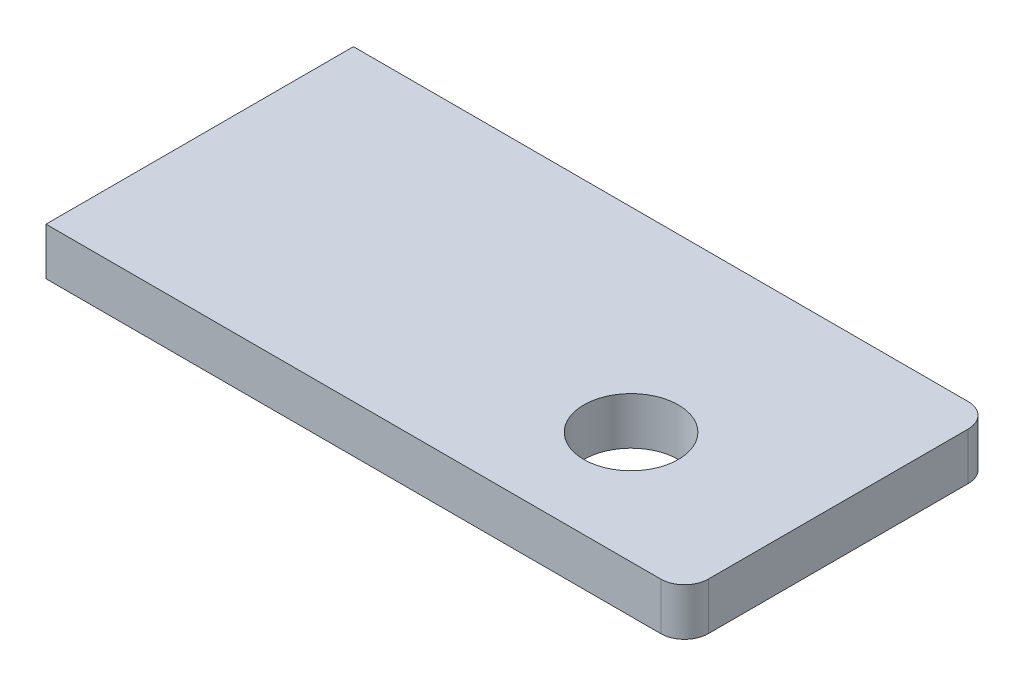
SolidWorks part; units mm, degrees
ref_plane "Front Plane" through (0, 0, 0) normal (0, 0, 1) x (1, 0, 0)
ref_plane "Top Plane" through (0, 0, 0) normal (0, 1, 0) x (1, 0, 0)
ref_plane "Right Plane" through (0, 0, 0) normal (1, 0, 0) x (0, 0, -1)
sketch "Sketch1" plane through (0, 0, 0) normal (0, 1, 0) x (1, 0, 0)
  line L0 (14.0275, 11.6358) -> (14.0275, 3.3874)
  line L1 (13.024, 11.6358) -> (-12.9725, 11.6358)
  line L2 (14.0275, 10.6324) -> (14.0275, -0.3607)
  line L3 (13.024, -1.3642) -> (-12.9725, -1.3642)
  line L4 (-12.9725, 11.6358) -> (-12.9725, -1.3642)
  arc A2 (14.0275, 10.6324) -> (13.024, 11.6358) centre (13.024, 10.6324) ccw
  arc A3 (13.024, -1.3642) -> (14.0275, -0.3607) centre (13.024, -0.3607) ccw
  circle A4 centre (7.0153, 3.3874) radius 2
  point P6 (-12.9725, 11.6358)
  point P11 (14.0275, 11.6358)
  point P14 (14.0275, -1.3642)
  dimension "D1" = 27
  dimension "D2" = 13
extrude "Boss-Extrude1" add sketch "Sketch1" along normal blind 2
